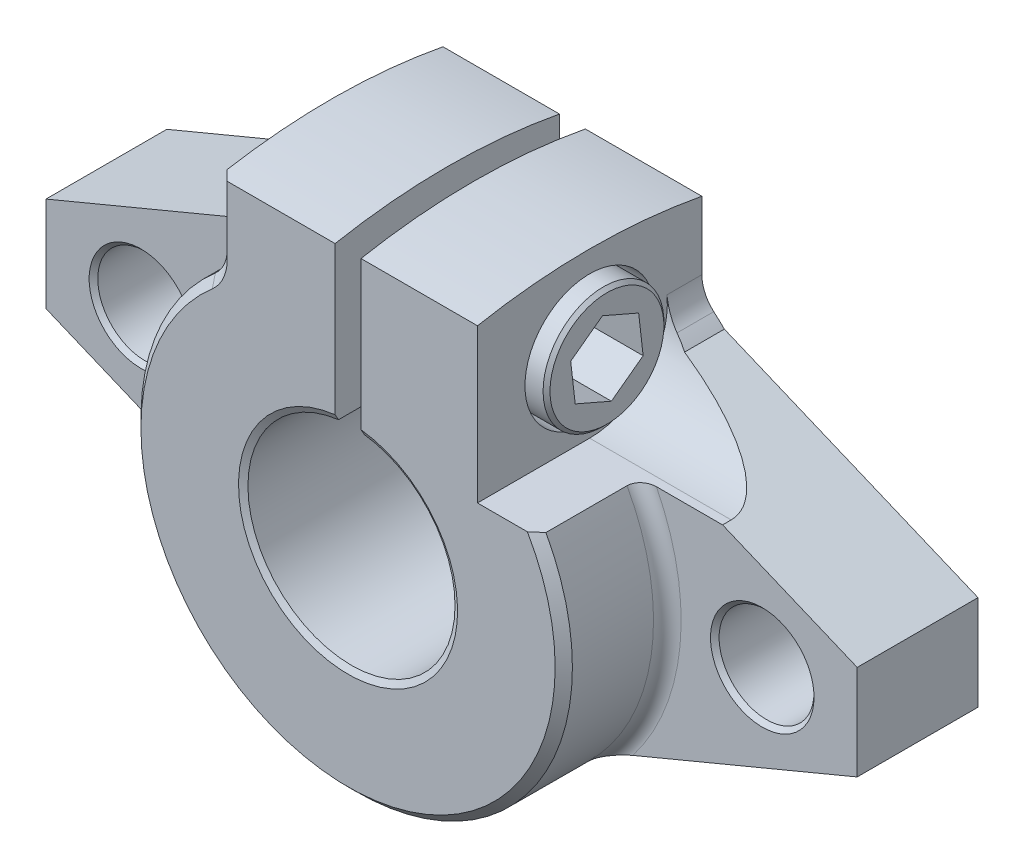
SolidWorks part; units mm, degrees
material "1060 Alloy"
ref_plane "Front Plane" through (0, 0, 0) normal (0, 0, 1) x (1, 0, 0)
ref_plane "Top Plane" through (0, 0, 0) normal (0, 1, 0) x (1, 0, 0)
ref_plane "Right Plane" through (0, 0, 0) normal (1, 0, 0) x (0, 0, -1)
sketch "Sketch1" plane through (0, 0, 0) normal (0, 0, 1) x (1, 0, 0)
  line L0 (0, 23.6454) -> (0, -19.4549) construction
  line L1 (0.75, 5.9529) -> (0.75, 15.5)
  line L2 (0.75, 15.5) -> (7.5, 15.5)
  line L3 (7.5, 15.5) -> (7.5, 10)
  line L4 (-7.5, 15.5) -> (-7.5, 10)
  line L5 (-0.75, 15.5) -> (-7.5, 15.5)
  line L6 (-0.75, 5.9529) -> (-0.75, 15.5)
  arc A0 (-0.75, 5.9529) -> (0.75, 5.9529) centre (0, 0) ccw
  arc A1 (-7.5, 10) -> (7.5, 10) centre (0, 0) ccw
  arc A2 (0, -6) -> (0.818, 5.944) centre (0, 0) ccw construction
  arc A3 (0, -12.5) -> (1.7041, 12.3833) centre (0, 0) ccw construction
  dimension "D1" = 6
  dimension "D3" = 1.5
  dimension "D4" = 15
  dimension "D5" = 28
  dimension "D2" = 6.5
extrude "Boss-Extrude1" add sketch "Sketch1" along normal blind 13
sketch "Sketch2" plane through (0, 0, 0) normal (1, 0, 0) x (0, 0, -1)
  line L0 (0, 10) -> (0, 15.5) construction
  line L1 (-13, 10) -> (-13, 15.5) construction
  line L2 (-6.5, 15.5) -> (-6.5, -4.9716) construction
  line L3 (-13, 15.5) -> (0, 15.5) construction
  arc A0 (0, 14.8911) -> (-13, 14.8911) centre (-6.5, -19.5) ccw
  dimension "D1" = 35
extrude "Cut-Extrude1" cut sketch "Sketch2" against normal through all and the other way through all flip side to cut
fillet "Fillet1" radius 2 2 edges at (-7.5, 10, 6.5) (7.5, 10, 6.5)
sketch "Sketch3" plane through (0, 0, 0) normal (0, 0, 1) x (1, 0, 0)
  line L0 (0, 19.2448) -> (0, 0) construction
  line L1 (0, 0) -> (32.3729, 0) construction
  line L2 (8.8035, 8.874) -> (23.5, 2.75)
  line L3 (23.5, 2.75) -> (23.5, -2.75)
  line L4 (8.8035, -8.874) -> (23.5, -2.75)
  line L5 (-23.5, 2.75) -> (-23.5, -2.75) construction
  arc A0 (-8.1897, 9.4435) -> (8.1897, 9.4435) centre (0, 0) ccw construction
  arc A1 (8.8035, 8.874) -> (8.8035, -8.874) centre (0, 0) cw
  arc A2 (-8.1897, 9.4435) -> (8.1897, 9.4435) centre (0, 0) ccw construction
  point P11 (23.5, 0)
  point P12 (18, 0)
  point P15 (-18, 0)
  dimension "D1" = 47
  dimension "D2" = 36
  dimension "D3" = 5.5
extrude "Boss-Extrude2" add sketch "Sketch3" along normal blind 7
mirror "Mirror1" about plane through (0, 0, 0) normal (1, 0, 0) of bodies 103
hole_wizard "Ø5.5 (5.5) Diameter Hole1" positions "Sketch5" profile "Sketch4" hole size "Ø5.5" standard "DIN"
sketch "Sketch5" plane through (0, 0, 7) normal (0, 0, 1) x (1, 0, 0)
  point P0 (18, 0)
  point P2 (-18, 0)
sketch "Sketch4" plane through (18, 0, 7) normal (1, 0, 0) x (0, -1, 0)
  line L0 (0, 0) -> (0, 11.6524)
  line L1 (0, 11.6524) -> (2.75, 10)
  line L2 (2.75, 10) -> (2.75, 0.25)
  line L3 (2.75, 0.25) -> (3, 0)
  line L5 (3, 0) -> (0, 0)
  line L6 (-2.75, 0.25) -> (-3, 0) construction
  line L10 (0, 11.6524) -> (-2.75, 10) construction
  line L11 (0, -6.35) -> (0, 107.95) construction
  dimension "Hole Dia." = 5.5
  dimension "Hole Depth" = 10
  dimension "Near C'Sink Dia." = 6
  dimension "Near C'Sink Angle" = 90
  dimension "Drill Angle" = 118
sketch "Sketch6" plane through (0, 0, 0) normal (1, 0, 0) x (0, 0, -1)
  line L0 (-6.5, -12.5) -> (-6.5, 18.0939) construction
  line L1 (-13, -12.5) -> (0, -12.5) construction
  arc A1 (0, 14.8911) -> (-13, 14.8911) centre (-6.5, -19.5) ccw construction
  point P0 (-6.5, 10.5)
  dimension "D1" = 5
sketch "Sketch9" plane through (7.5, 0, 0) normal (1, 0, 0) x (0, 0, -1)
  line L0 (-6.5, -12.5) -> (-6.5, 18.0939) construction
  line L2 (-13, 10.9545) -> (0, 10.9545) construction
  line L3 (-2.023, 10.9545) -> (-13, 10.9545)
  line L4 (-13, 10.9545) -> (-13, 6)
  line L5 (-13, 9.4435) -> (-13, -12.5) construction
  line L6 (-13, 6) -> (-6.5, 6)
  arc A0 (-6.5, 6) -> (-2.023, 10.9545) centre (-6.5, 10.5) ccw
  dimension "D1" = 4.5
extrude "Cut-Extrude2" cut sketch "Sketch9" along normal up to next
hole_wizard "CBORE for M4 Hex Socket Head Cap Screw3" positions "Sketch11" profile "Sketch10" counterbore size "M4" standard "DIN" end condition through all
sketch "Sketch11" plane through (7.5, 0, 0) normal (1, 0, 0) x (0, 0, -1)
  point P0 (-6.5, 10.5)
sketch "Sketch10" plane through (7.5, 10.5, 6.5) normal (0, 1, 0) x (0, 0, -1)
  line L0 (0, 0) -> (0, 31)
  line L1 (0, 31) -> (1.7, 31)
  line L3 (1.7, 31) -> (1.7, 3)
  line L4 (1.7, 3) -> (3.75, 3)
  line L5 (3.75, 3) -> (3.75, 0)
  line L7 (3.75, 0) -> (0, 0)
  line L11 (0, -6.35) -> (0, 107.95) construction
  dimension "Thru Hole Dia." = 3.4
  dimension "Thru Hole Depth" = 31
  dimension "C'Bore Dia." = 7.5
  dimension "C'Bore Depth" = 3
ref_plane "Plane1" through (0, 0, 6.5) normal (0, 0, 1) x (1, 0, 0)
sketch "Sketch12" plane through (0, 0, 6.5) normal (0, 0, 1) x (1, 0, 0)
  line L0 (0, 10.5) -> (19.7633, 10.5) construction
  line L1 (4.5, 14) -> (8.5, 14)
  line L2 (8.5, 14) -> (8.5, 10.5)
  line L3 (8.5, 10.5) -> (-5.5, 10.5)
  line L4 (-5.5, 10.5) -> (-5.5, 12)
  line L5 (-5.5, 12) -> (-5, 12.5)
  line L6 (-5, 12.5) -> (4.5, 12.5)
  line L7 (4.5, 12.5) -> (4.5, 14)
  line L8 (4.5, 7) -> (8.5, 7) construction
  line L9 (-5, 8.5) -> (4.5, 8.5) construction
  line L10 (4.5, 8.8) -> (4.5, 12.2) construction
  line L11 (4.5, 8.8) -> (4.5, 12.2) construction
  dimension "D1" = 7
  dimension "D2" = 4
  dimension "D3" = 4
  dimension "D4" = 0.5
  dimension "D5" = 10
  dimension "D6" = 45
revolve "Revolve1" add sketch "Sketch12" angle 360 about L0
chamfer "Chamfer1" distance 0.2 angle 45 1 edges at (8.5, 10.5, 10)
sketch "Sketch13" plane through (8.5, 0, 0) normal (1, 0, 0) x (0, 0, -1)
  line L1 (-4.6615, 11.8612) -> (-6.7596, 12.7728)
  line L2 (-6.7596, 12.7728) -> (-8.5981, 11.4116)
  line L3 (-8.5981, 11.4116) -> (-8.3385, 9.1388)
  line L4 (-8.3385, 9.1388) -> (-6.2404, 8.2272)
  line L5 (-6.2404, 8.2272) -> (-4.4019, 9.5884)
  line L6 (-4.4019, 9.5884) -> (-4.6615, 11.8612)
  circle A0 centre (-6.5, 10.5) radius 1.9811 construction
extrude "Cut-Extrude3" cut sketch "Sketch13" against normal blind 3
chamfer "Chamfer2" distance 0.5 angle 45 3 edges at (-7.5, 12.9228, 13) (-7.6806, 10.124, 13) (-2.2116, -12.3028, 13)
fillet "Fillet2" radius 0.8 4 edges at (-12.5, 0, 7) (8.8035, -8.874, 3.5) (-8.8035, -8.874, 3.5) (12.37, -1.7983, 7)
chamfer "Chamfer3" distance 0.2 angle 60 1 edges at (0, -6, 13)
